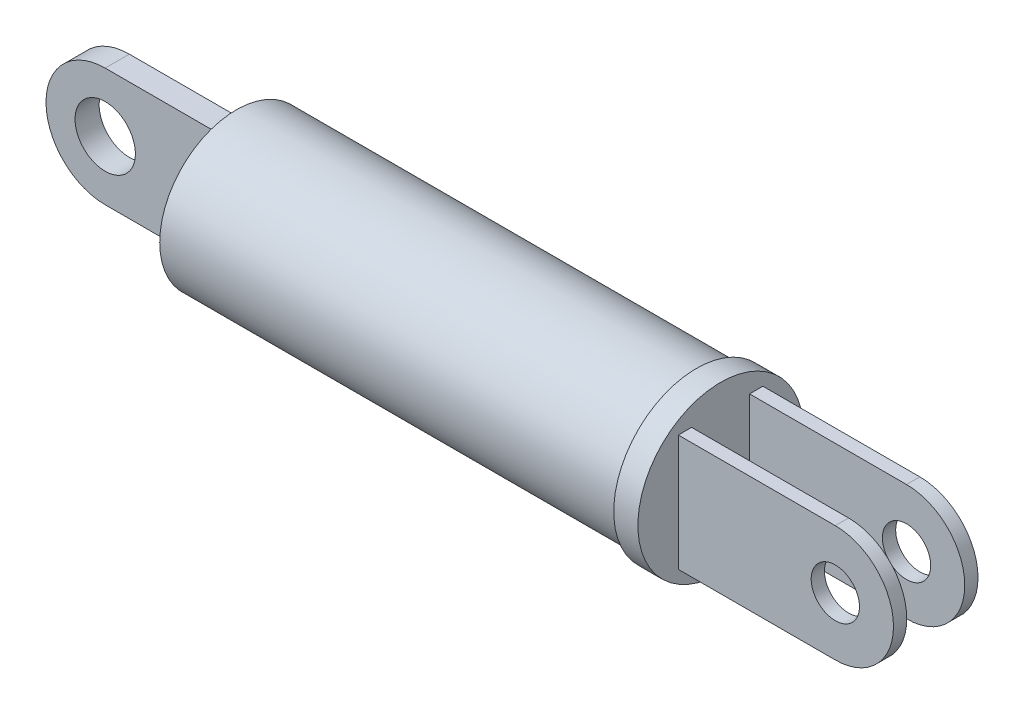
SolidWorks part; units mm, degrees
material "Cast Stainless Steel"
ref_plane "Front Plane" through (0, 0, 0) normal (0, 0, 1) x (1, 0, 0)
ref_plane "Top Plane" through (0, 0, 0) normal (0, 1, 0) x (1, 0, 0)
ref_plane "Right Plane" through (0, 0, 0) normal (1, 0, 0) x (0, 0, -1)
sketch "Sketch1" plane through (0, 0, 0) normal (1, 0, 0) x (0, 0, -1)
  circle A0 centre (0, 0) radius 12.7
  dimension "D1" = 25.4
extrude "Extrude1" add sketch "Sketch1" along normal blind 76.2
sketch "Sketch2" plane through (0, 0, 0) normal (0, 0, 1) x (1, 0, 0)
  line L0 (0, 0) -> (-32.8673, 0) construction
  line L1 (15.07, 0) -> (-15.07, 0) construction
  line L2 (0, 9.8057) -> (-19.7331, 9.8057)
  line L3 (0, 12.7) -> (0, -12.7) construction
  line L4 (0, -9.8057) -> (-19.7331, -9.8057)
  line L5 (0, 9.8057) -> (0, -9.8057)
  arc A0 (-19.7331, 9.8057) -> (-19.7331, -9.8057) centre (-19.7331, 0) ccw
  circle A1 centre (-19.7331, 0) radius 5
  dimension "D1" = 10
extrude "Extrude2" add sketch "Sketch2" along normal mid plane 4
sketch "Sketch3" plane through (76.2, 0, 0) normal (1, 0, 0) x (0, 0, -1)
  circle A2 centre (0, 0) radius 13.7
  circle A3 centre (0, 0) radius 13.7
  dimension "D1" = 1
extrude "Extrude3" add sketch "Sketch3" along normal blind 4
sketch "Sketch4" plane through (0, 0, 0) normal (0, 0, 1) x (1, 0, 0)
  line L0 (80.2, 9.6357) -> (106.2, 9.6357)
  line L1 (80.2, -13.7) -> (80.2, 13.7) construction
  line L2 (331.2897, 0) -> (364.956, 0) construction
  line L3 (80.2, -9.6357) -> (106.2, -9.6357)
  line L4 (80.2, 9.6357) -> (80.2, -9.6357)
  arc A0 (106.2, 9.6357) -> (106.2, -9.6357) centre (106.2, 0) cw
  circle A1 centre (106.2, 0) radius 4
  dimension "D1" = 8
  dimension "D2" = 26
extrude "Extrude4" add sketch "Sketch4" along normal mid plane 14
sketch "Sketch5" plane through (0, 0, 0) normal (0, 1, 0) x (1, 0, 0)
  line L0 (302.6802, 0) -> (363.3519, 0) construction
  line L1 (-15.07, 0) -> (15.07, 0) construction
  line L2 (80.2, -13.7) -> (80.2, 13.7) construction
  line L3 (80.2, 4.8012) -> (359.728, 4.8012)
  line L4 (80.2, 4.8012) -> (80.2, -4.8012)
  line L5 (80.2, -4.8012) -> (359.728, -4.8012)
  line L6 (359.728, 4.8012) -> (359.728, -4.8012)
  line L7 (359.728, 0) -> (80.2, 0) construction
extrude "Cut-Extrude1" cut sketch "Sketch5" against normal through all and the other way through all
